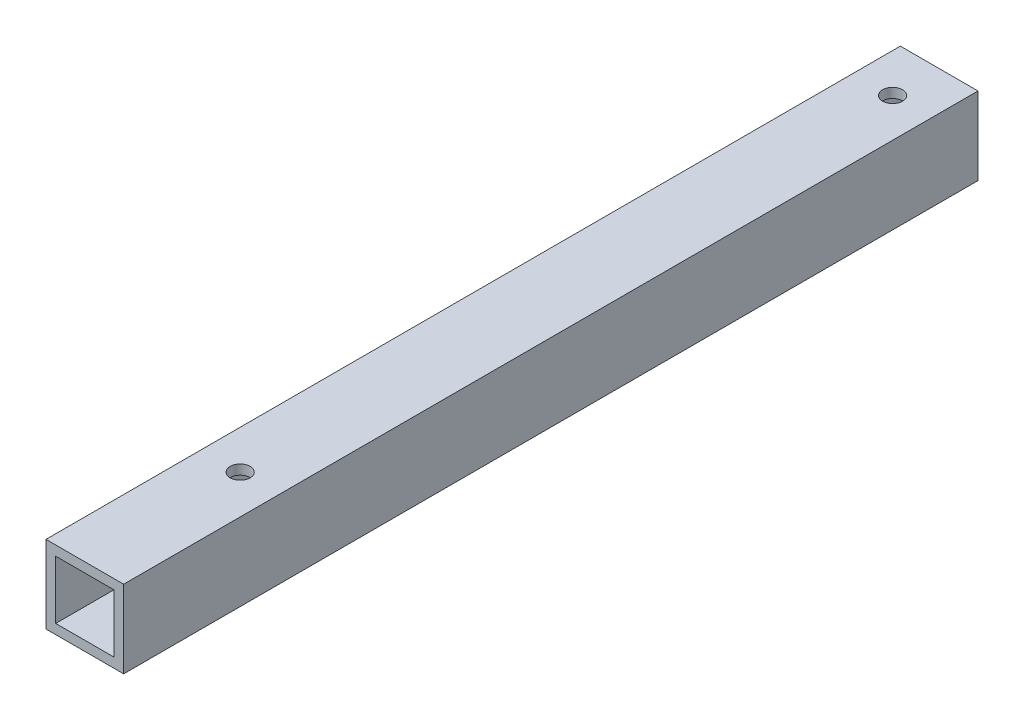
SolidWorks part; units mm, degrees
material "1060 Alloy"
ref_plane "Front Plane" through (0, 0, 0) normal (0, 0, 1) x (1, 0, 0)
ref_plane "Top Plane" through (0, 0, 0) normal (0, 1, 0) x (1, 0, 0)
ref_plane "Right Plane" through (0, 0, 0) normal (1, 0, 0) x (0, 0, -1)
sketch "Sketch2" plane through (0, 0, 0) normal (0, 0, 1) x (1, 0, 0)
  line L1 (12.7, -12.7) -> (-12.7, -12.7)
  line L2 (12.7, -12.7) -> (12.7, 12.7)
  line L3 (12.7, 12.7) -> (-12.7, 12.7)
  line L4 (-12.7, -12.7) -> (-12.7, 12.7)
  line L5 (12.7, -12.7) -> (-12.7, 12.7) construction
  line L6 (12.7, 12.7) -> (-12.7, -12.7) construction
  point P0 (0, 0)
  dimension "D1" = 25.4
extrude "Boss-Extrude1" add sketch "Sketch2" along normal blind 279.4 contours L4 L3 L2 L1
sketch "Sketch4" plane through (0, 0, 0) normal (0, 0, 1) x (1, 0, 0)
  line L0 (12.7, -12.7) -> (12.7, 12.7) construction
  line L1 (-9.525, -9.525) -> (9.525, -9.525)
  line L2 (-9.525, -9.525) -> (-9.525, 9.525)
  line L3 (-9.525, 9.525) -> (9.525, 9.525)
  line L4 (9.525, -9.525) -> (9.525, 9.525)
  line L5 (-9.525, -9.525) -> (9.525, 9.525) construction
  line L6 (-9.525, 9.525) -> (9.525, -9.525) construction
  line L7 (12.7, 12.7) -> (-12.7, 12.7) construction
  point P0 (0, 0)
  dimension "D1" = 3.175
  dimension "D2" = 3.175
extrude "Cut-Extrude1" cut sketch "Sketch4" along normal through all
sketch "Sketch5" plane through (0, 12.7, 0) normal (0, 1, 0) x (1, 0, 0)
  line L0 (12.7, 0) -> (-12.7, 0) construction
  circle A0 centre (0, -15.24) radius 3.2639
  point P5 (0, 0)
  dimension "D1" = 6.5278
  dimension "D2" = 15.24
extrude "Cut-Extrude2" cut sketch "Sketch5" against normal through all
sketch "Sketch6" plane through (0, 12.7, 0) normal (0, 1, 0) x (1, 0, 0)
  line L0 (12.7, -279.4) -> (-12.7, -279.4) construction
  circle A0 centre (0, -228.6) radius 3.2639
  point P4 (0, -279.4)
  dimension "D1" = 6.5278
  dimension "D2" = 50.8
extrude "Cut-Extrude3" cut sketch "Sketch6" against normal through all
